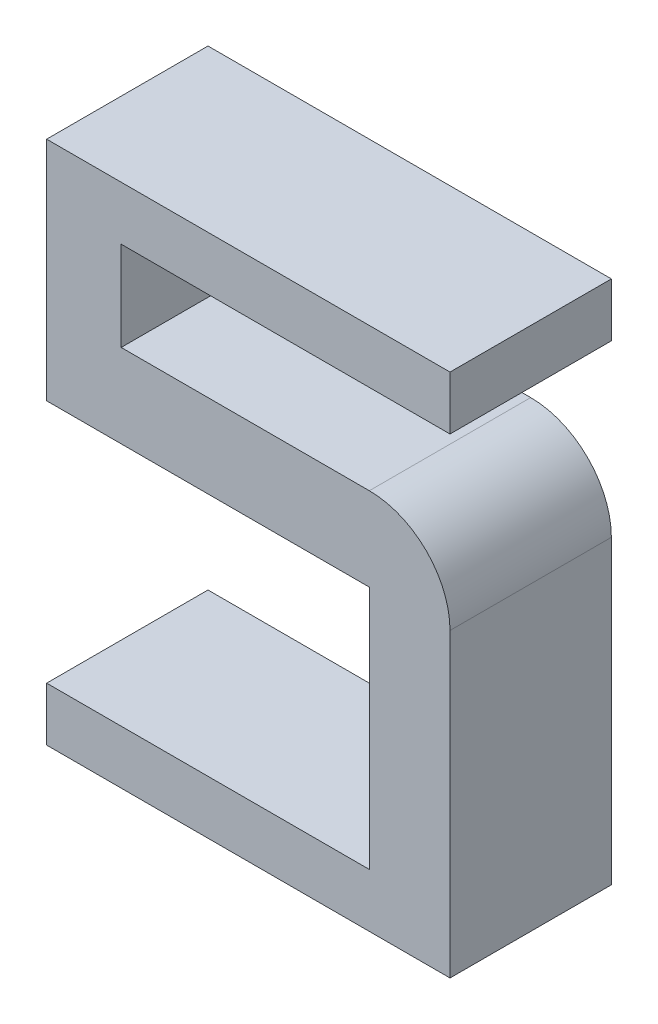
SolidWorks part; units mm, degrees
ref_plane "Front Plane" through (0, 0, 0) normal (0, 0, 1) x (1, 0, 0)
ref_plane "Top Plane" through (0, 0, 0) normal (0, 1, 0) x (1, 0, 0)
ref_plane "Right Plane" through (0, 0, 0) normal (1, 0, 0) x (0, 0, -1)
sketch "Sketch1" plane through (0, 0, 0) normal (0, 0, 1) x (1, 0, 0)
  line L52 (130.8348, 133.2285) -> (80.8348, 133.2285)
  line L53 (80.8348, 133.2285) -> (80.8348, 105.1403)
  line L54 (80.8348, 105.1403) -> (120.8348, 105.1403)
  line L55 (120.8348, 105.1403) -> (120.8348, 74.8346)
  line L56 (120.8348, 74.8346) -> (80.8348, 74.8346)
  line L57 (80.8348, 74.8346) -> (80.8348, 68.1821)
  line L58 (80.8348, 68.1821) -> (130.8348, 68.1821)
  line L59 (130.8348, 68.1821) -> (130.8348, 105.4886)
  line L60 (120.8348, 115.4886) -> (90.0743, 115.4886)
  line L61 (90.0743, 115.4886) -> (90.0743, 126.576)
  line L62 (90.0743, 126.576) -> (130.8348, 126.576)
  line L63 (130.8348, 126.576) -> (130.8348, 133.2285)
  arc A4 (130.8348, 105.4886) -> (120.8348, 115.4886) centre (120.8348, 105.4886) ccw
extrude "Boss-Extrude1" add sketch "Sketch1" along normal blind 20 contours L52 L53 L54 L55 L56 L57 L58 L59 A4 L60 L61 L62 L63
